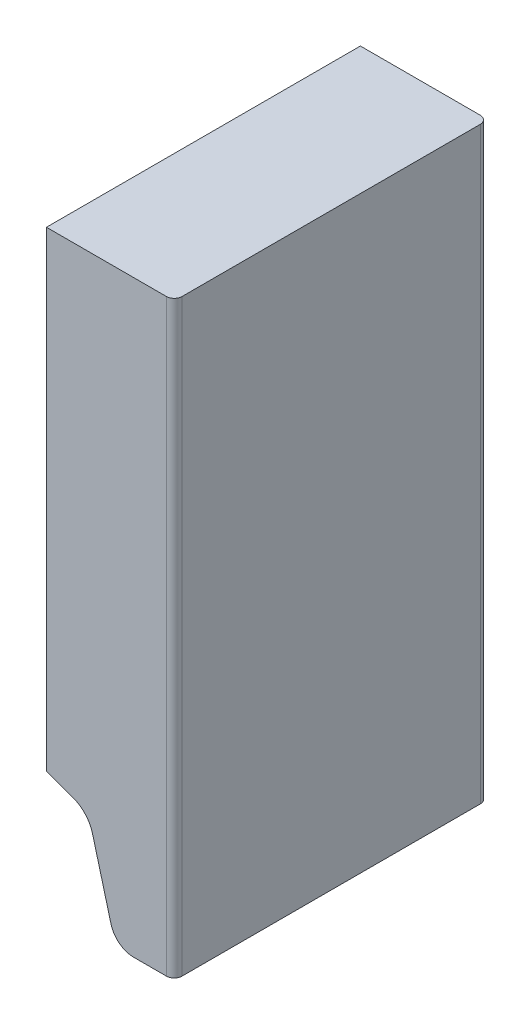
SolidWorks part; units mm, degrees
material "K110"
ref_plane "Front Plane" through (0, 0, 0) normal (0, 0, 1) x (1, 0, 0)
ref_plane "Top Plane" through (0, 0, 0) normal (0, 1, 0) x (1, 0, 0)
ref_plane "Right Plane" through (0, 0, 0) normal (1, 0, 0) x (0, 0, -1)
sketch "Sketch1" plane through (0, 0, 0) normal (0, 1, 0) x (1, 0, 0)
  line L1 (-8.14, -20) -> (8.14, -20)
  line L2 (-8.14, -20) -> (-8.14, 20)
  line L3 (-8.14, 20) -> (8.14, 20)
  line L4 (8.14, -20) -> (8.14, 20)
  line L5 (-8.14, -20) -> (8.14, 20) construction
  line L6 (-8.14, 20) -> (8.14, -20) construction
  point P0 (0, 0)
  dimension "D1" = 16.28
  dimension "D2" = 40
extrude "Boss-Extrude1" add sketch "Sketch1" against normal blind 75
sketch "Sketch2" plane through (0, 0, 20) normal (0, 0, 1) x (1, 0, 0)
  line L0 (-8.14, 0) -> (8.14, 0) construction
  line L1 (-8.14, -75) -> (-2.14, -75) construction
  line L2 (-8.14, -75) -> (-8.14, -61) construction
  line L3 (-8.14, -61) -> (-6.14, -61) construction
  line L4 (-2.14, -75) -> (-2.14, -65) construction
  line L5 (8.14, -75) -> (8.14, 0) construction
  line L6 (-4.7719, -61.2412) -> (-8.14, -60.0153)
  line L7 (-8.14, -75) -> (-8.14, 0) construction
  line L9 (0.6806, -75) -> (-8.14, -75)
  line L10 (-8.14, -75) -> (-8.14, -60.0153)
  line L11 (-2.2763, -63.9647) -> (0.6806, -75)
  line L12 (-8.14, -75) -> (8.14, -75) construction
  arc A0 (-6.14, -61) -> (-2.14, -65) centre (-6.14, -65) cw construction
  arc A1 (-2.2763, -63.9647) -> (-4.7719, -61.2412) centre (-6.14, -65) ccw
  arc A2 (-2.14, -65) -> (-2.2763, -63.9647) centre (-6.14, -65) ccw construction
  dimension "D3" = 4
  dimension "D1" = 61
  dimension "D2" = 10.28
  dimension "D4" = 2
  dimension "D5" = 20
  dimension "D6" = 15
extrude "Cut-Extrude1" cut sketch "Sketch2" against normal up to next
fillet "Fillet1" radius 3 1 edges at (0.6806, -75, 0)
fillet "Fillet2" radius 1 2 edges at (8.14, -37.5, -20) (8.14, -37.5, 20)
